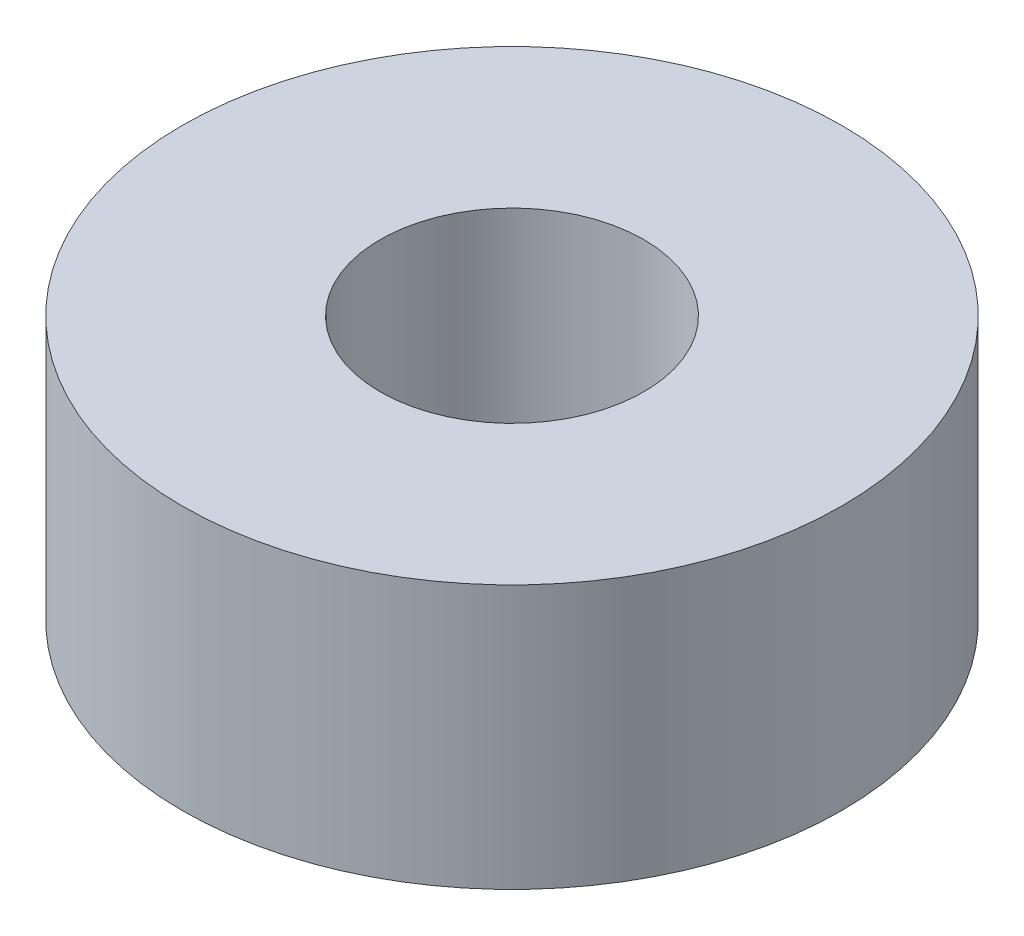
SolidWorks part; units mm, degrees
material "6061 合金"
ref_plane "前视基准面" through (0, 0, 0) normal (0, 0, 1) x (1, 0, 0)
ref_plane "上视基准面" through (0, 0, 0) normal (0, 1, 0) x (1, 0, 0)
ref_plane "右视基准面" through (0, 0, 0) normal (1, 0, 0) x (0, 0, -1)
other "Configuration Table"
sketch "草图1" plane through (0, 0, 0) normal (0, 1, 0) x (1, 0, 0)
  circle A0 centre (0, 0) radius 5
  circle A1 centre (0, 0) radius 2
  dimension "D1" = 10
extrude "凸台-拉伸1" add sketch "草图1" along normal blind 4
